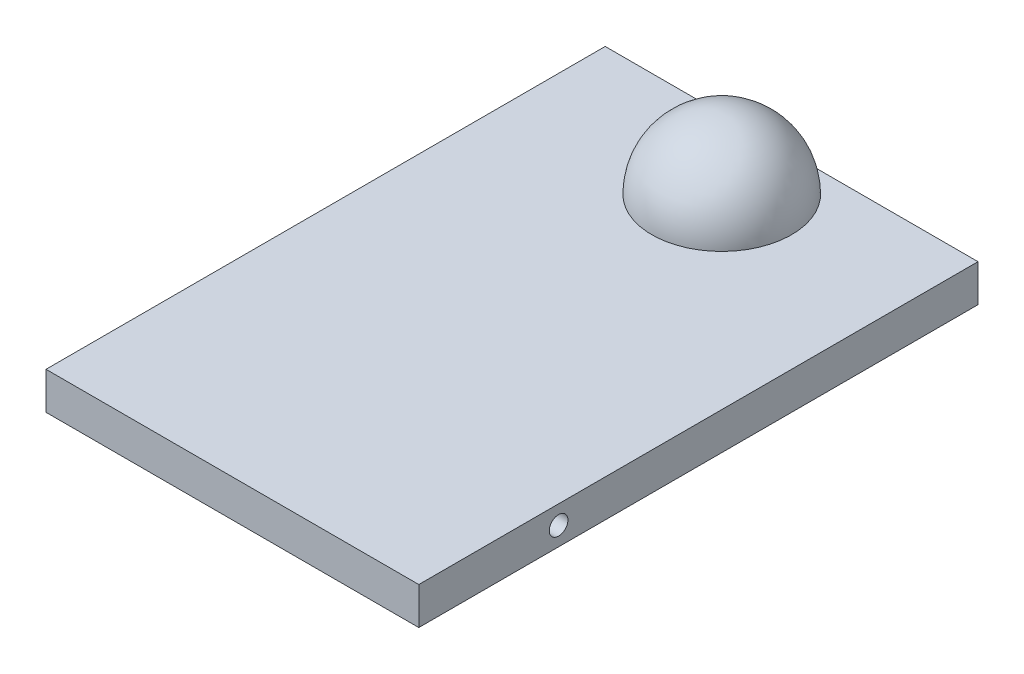
SolidWorks part; units mm, degrees
ref_plane "前基準面" through (0, 0, 0) normal (0, 0, 1) x (1, 0, 0)
ref_plane "上基準面" through (0, 0, 0) normal (0, 1, 0) x (1, 0, 0)
ref_plane "右基準面" through (0, 0, 0) normal (1, 0, 0) x (0, 0, -1)
sketch "草圖1" plane through (0, 0, 0) normal (0, 1, 0) x (1, 0, 0)
  line L1 (-50, 75) -> (50, 75)
  line L2 (-50, 75) -> (-50, -75)
  line L3 (-50, -75) -> (50, -75)
  line L4 (50, 75) -> (50, -75)
  line L5 (-50, 75) -> (50, -75) construction
  line L6 (-50, -75) -> (50, 75) construction
  point P0 (0, 0)
  dimension "D1" = 100
  dimension "D2" = 150
extrude "填料-伸長1" add sketch "草圖1" along normal blind 10
sketch "草圖2" plane through (0, 10, 0) normal (0, 1, 0) x (1, 0, 0)
  line L0 (0, 75) -> (0, 0) construction
  line L1 (50, 75) -> (-50, 75) construction
  line L2 (0, 75) -> (0, 37.5)
  arc A0 (0, 75) -> (0, 37.5) centre (0, 56.25) cw
revolve "旋轉2" add sketch "草圖2" angle 180 about L0
sketch "草圖3" plane through (-50, 0, 0) normal (-1, 0, 0) x (0, 0, 1)
  line L0 (75, 5) -> (0, 5) construction
  line L1 (75, 10) -> (75, 0) construction
  circle A0 centre (37.5, 5) radius 2.5
  dimension "D1" = 5
extrude "除料-伸長1" cut sketch "草圖3" against normal through all
